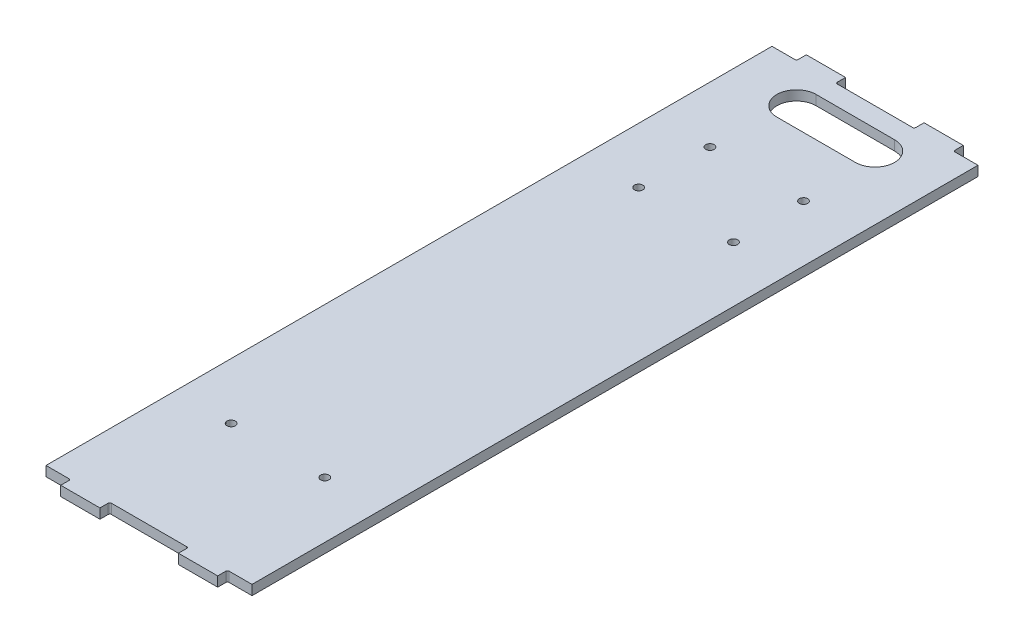
SolidWorks part; units mm, degrees
ref_plane "Front Plane" through (0, 0, 0) normal (0, 0, 1) x (1, 0, 0)
ref_plane "Top Plane" through (0, 0, 0) normal (0, 1, 0) x (1, 0, 0)
ref_plane "Right Plane" through (0, 0, 0) normal (1, 0, 0) x (0, 0, -1)
sketch "Sketch1" plane through (0, 0, 0) normal (0, 1, 0) x (1, 0, 0)
  line L1 (33.3375, -117.475) -> (-33.3375, -117.475)
  line L2 (33.3375, -117.475) -> (33.3375, 117.475)
  line L3 (33.3375, 117.475) -> (-33.3375, 117.475)
  line L4 (-33.3375, -117.475) -> (-33.3375, 117.475)
  line L5 (33.3375, -117.475) -> (-33.3375, 117.475) construction
  line L6 (33.3375, 117.475) -> (-33.3375, -117.475) construction
  point P0 (0, 0)
  dimension "D1" = 234.95
  dimension "D2" = 66.675
extrude "Boss-Extrude1" add sketch "Sketch1" along normal blind 3.175
sketch "Sketch3" plane through (0, 3.175, 0) normal (0, 1, 0) x (1, 0, 0)
  line L0 (-33.3375, -117.475) -> (33.3375, -117.475) construction
  line L1 (-25.4, -117.475) -> (-12.7, -117.475)
  line L2 (-25.4, -117.475) -> (-25.4, -120.65)
  line L3 (-25.4, -120.65) -> (-12.7, -120.65)
  line L4 (-12.7, -117.475) -> (-12.7, -120.65)
  line L5 (25.4, -120.65) -> (12.7, -120.65)
  line L6 (25.4, -120.65) -> (25.4, -117.475)
  line L7 (25.4, -117.475) -> (12.7, -117.475)
  line L8 (12.7, -120.65) -> (12.7, -117.475)
  line L9 (-33.3375, 0) -> (33.3375, 0) construction
  line L10 (-33.3375, 117.475) -> (-33.3375, -117.475) construction
  line L11 (33.3375, -117.475) -> (33.3375, 117.475) construction
  line L12 (0, 0) -> (0, 50000) construction
  line L13 (12.7, 120.65) -> (12.7, 117.475)
  line L14 (25.4, 117.475) -> (12.7, 117.475)
  line L15 (25.4, 120.65) -> (25.4, 117.475)
  line L16 (25.4, 120.65) -> (12.7, 120.65)
  line L17 (-12.7, 117.475) -> (-12.7, 120.65)
  line L18 (-25.4, 120.65) -> (-12.7, 120.65)
  line L19 (-25.4, 117.475) -> (-25.4, 120.65)
  line L20 (-25.4, 117.475) -> (-12.7, 117.475)
  dimension "D1" = 12.7
  dimension "D2" = 3.175
  dimension "D3" = 25.4
extrude "Boss-Extrude2" add sketch "Sketch3" against normal up to surface (3.175 mm away) up to face at (0, 0, 0)
sketch "Sketch4" plane through (0, 3.175, 0) normal (0, 1, 0) x (1, 0, 0)
  line L0 (-12.7, 104.775) -> (12.7, 104.775) construction
  line L1 (-12.7, 111.125) -> (12.7, 111.125)
  line L2 (-12.7, 98.425) -> (12.7, 98.425)
  line L4 (12.7, 117.475) -> (-12.7, 117.475) construction
  arc A0 (-12.7, 111.125) -> (-12.7, 98.425) centre (-12.7, 104.775) ccw
  arc A1 (12.7, 98.425) -> (12.7, 111.125) centre (12.7, 104.775) ccw
  point P2 (0, 104.775)
  dimension "D2" = 6.35
  dimension "D1" = 12.7
  dimension "D3" = 25.4
extrude "Cut-Extrude1" cut sketch "Sketch4" against normal through all
fillet "Fillet1" radius 0.508 8 edges at (25.4, 1.5875, 117.475) (12.7, 1.5875, 117.475) (-12.7, 1.5875, -117.475) (-25.4, 1.5875, -117.475)
sketch "Sketch6" plane through (0, 3.175, 0) normal (0, 1, 0) x (1, 0, 0)
  line L0 (63.5, 109.6229) -> (63.5, -72.1696) construction
  line L1 (-33.3375, 117.475) -> (-33.3375, -117.475) construction
  line L2 (-33.3375, -117.475) -> (-25.908, -117.475) construction
  line L3 (148.5, -80.645) -> (-21.5, -80.645) construction
  line L4 (148.5, -80.645) -> (148.5, 89.355) construction
  line L5 (148.5, 89.355) -> (-21.5, 89.355) construction
  line L6 (-21.5, -80.645) -> (-21.5, 89.355) construction
  line L7 (148.5, -80.645) -> (-21.5, 89.355) construction
  line L8 (148.5, 89.355) -> (-21.5, -80.645) construction
  line L9 (-21.5, 4.355) -> (148.5, 4.355) construction
  line L10 (0, 0) -> (0, -117.475) construction
  line L11 (-12.192, -117.475) -> (12.192, -117.475) construction
  point P4 (63.5, 4.355)
  point P12 (-15.15, 79.195)
  point P14 (-15.15, -75.745)
  point P15 (142.33, -75.745)
  point P16 (15.15, 79.195)
  point P17 (15.33, 56.335)
  point P18 (142.33, 56.335)
  point P19 (15.15, -75.745)
  point P20 (-15.33, 56.335)
  point P21 (142.15, 79.195)
  dimension "D1" = 96.8375
  dimension "D2" = 170
  dimension "D3" = 36.83
  dimension "D4" = 6.35
  dimension "D5" = 10.16
  dimension "D6" = 154.94
  dimension "D7" = 157.48
  dimension "D8" = 22.86
hole_wizard "#6-32 Tapped Hole1" positions "3DSketch1" profile "Sketch7" tap size "#6-32" standard "ANSI Inch" end condition through all
sketch3d "3DSketch1"
  point P0 (-15.15, 3.175, -79.195)
  point P3 (-15.33, 3.175, -56.335)
  point P6 (-15.15, 3.175, 75.745)
  point P33 (15.15, 3.175, -79.195)
  point P36 (15.33, 3.175, -56.335)
  point P39 (15.15, 3.175, 75.745)
sketch "Sketch7" plane through (-15.15, 3.175, -79.195) normal (1, 0, 0) x (0, 0, 1)
  line L0 (0, 0) -> (0, 3.175)
  line L1 (0, 3.175) -> (1.3525, 3.175)
  line L2 (1.3525, 3.175) -> (1.3525, 0)
  line L5 (1.3525, 0) -> (0, 0)
  line L11 (0, -6.35) -> (0, 107.95) construction
  dimension "Thread Major Dia." = 2.7051
  dimension "Thru Tap Drill Depth" = 3.175
